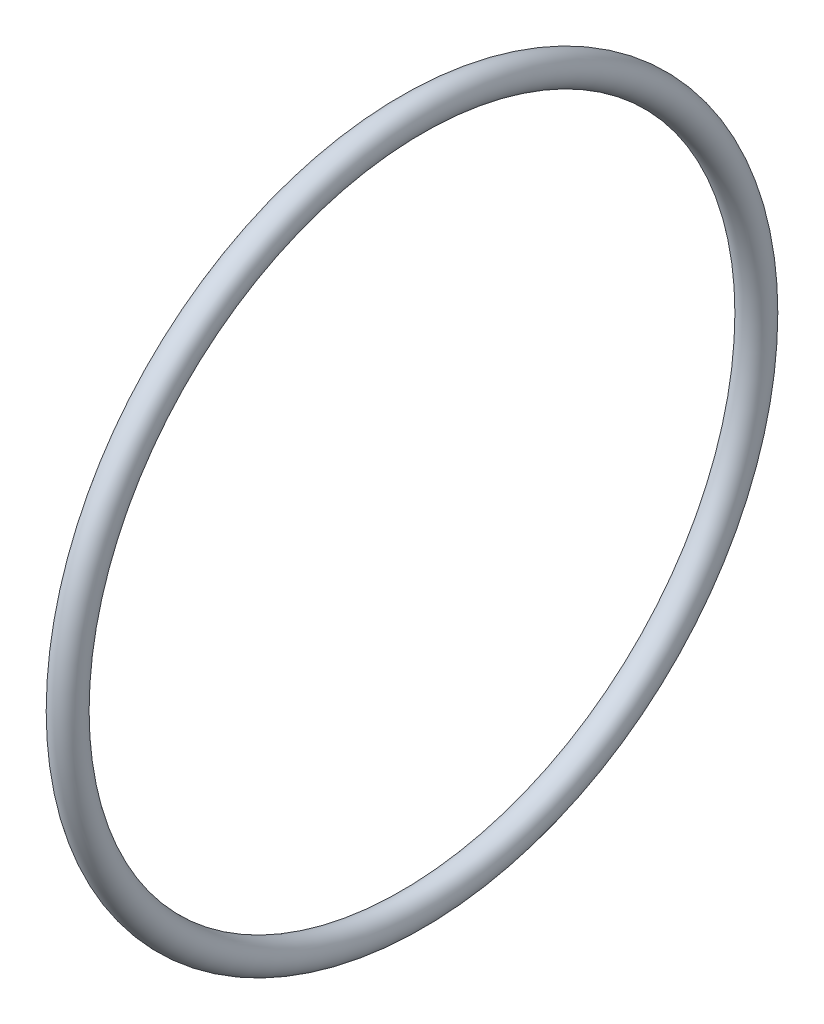
SolidWorks part; units mm, degrees
material "HYPALON"
ref_plane "Front Plane" through (0, 0, 0) normal (0, 0, 1) x (1, 0, 0)
ref_plane "Top Plane" through (0, 0, 0) normal (0, 1, 0) x (1, 0, 0)
ref_plane "Right Plane" through (0, 0, 0) normal (1, 0, 0) x (0, 0, -1)
sketch "Sketch2" plane through (0, 0, 0) normal (0, 0, 1) x (1, 0, 0)
  line L0 (0, 0) -> (15.7303, 0) construction
  circle A0 centre (0, 36) radius 1.5875
  dimension "D1" = 3.175
  dimension "D2" = 36
revolve "Revolve1" add sketch "Sketch2" angle 360 about L0
